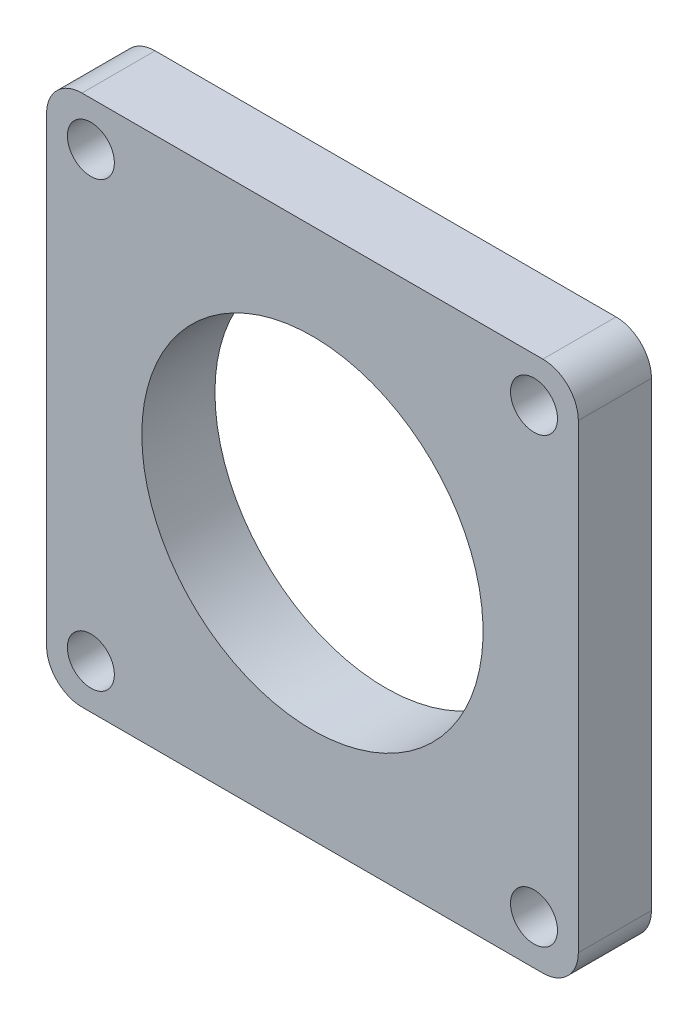
SolidWorks part; units mm, degrees
ref_plane "Front Plane" through (0, 0, 0) normal (0, 0, 1) x (1, 0, 0)
ref_plane "Top Plane" through (0, 0, 0) normal (0, 1, 0) x (1, 0, 0)
ref_plane "Right Plane" through (0, 0, 0) normal (1, 0, 0) x (0, 0, -1)
sketch "Sketch1" plane through (0, 0, 0) normal (0, 0, 1) x (1, 0, 0)
  line L0 (30, -26) -> (30, 26)
  line L1 (26, 30) -> (-26, 30)
  line L2 (-30, 26) -> (-30, -26)
  line L3 (-26, -30) -> (26, -30)
  line L4 (-25, 25) -> (25, -25) construction
  line L5 (25, 25) -> (-25, -25) construction
  line L6 (0, 30) -> (0, -30) construction
  line L7 (-30, 0) -> (30, 0) construction
  circle A0 centre (0, 0) radius 19.25
  circle A1 centre (-25, -25) radius 2.65
  circle A2 centre (-25, 25) radius 2.65
  circle A3 centre (25, -25) radius 2.65
  circle A4 centre (25, 25) radius 2.65
  arc A5 (30, 26) -> (26, 30) centre (26, 26) ccw
  arc A6 (-26, 30) -> (-30, 26) centre (-26, 26) ccw
  arc A7 (-30, -26) -> (-26, -30) centre (-26, -26) ccw
  arc A8 (26, -30) -> (30, -26) centre (26, -26) ccw
  point P28 (0, 0)
  point P29 (0, 0)
  dimension "D1" = 38.5
  dimension "D2" = 5.3
  dimension "D3" = 4
  dimension "D4" = 60
  dimension "D5" = 60
  dimension "D6" = 50
  dimension "D7" = 50
extrude "Boss-Extrude1" add sketch "Sketch1" against normal mid plane 8.25
equation "\"D7@Sketch1\"=\"D6@Sketch1\""
equation "\"D4@Sketch1\"=\"D5@Sketch1\""
